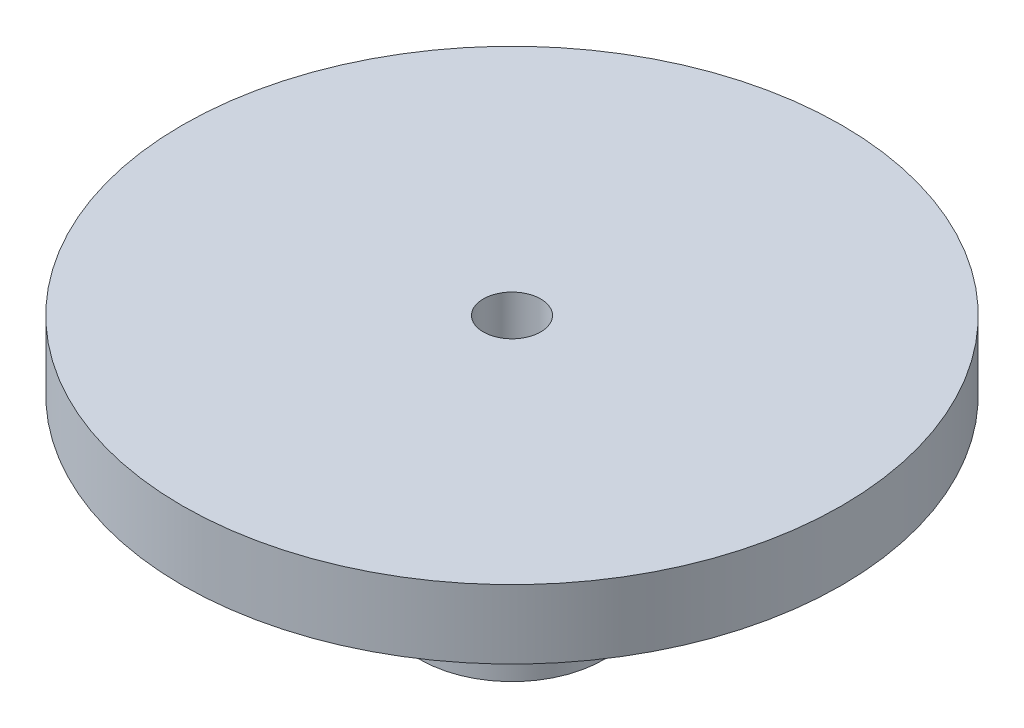
SolidWorks part; units mm, degrees
ref_plane "Front Plane" through (0, 0, 0) normal (0, 0, 1) x (1, 0, 0)
ref_plane "Top Plane" through (0, 0, 0) normal (0, 1, 0) x (1, 0, 0)
ref_plane "Right Plane" through (0, 0, 0) normal (1, 0, 0) x (0, 0, -1)
sketch "Sketch1" plane through (0, 0, 0) normal (0, 1, 0) x (1, 0, 0)
  circle A0 centre (0, 0) radius 2.5
  circle A1 centre (0, 0) radius 8
extrude "Boss-Extrude1" add sketch "Sketch1" along normal blind 16
sketch "Sketch2" plane through (0, 16, 0) normal (0, 1, 0) x (1, 0, 0)
  circle A0 centre (0, 0) radius 28.75
  circle A1 centre (0, 0) radius 2.5
extrude "Boss-Extrude2" add sketch "Sketch2" along normal blind 6
